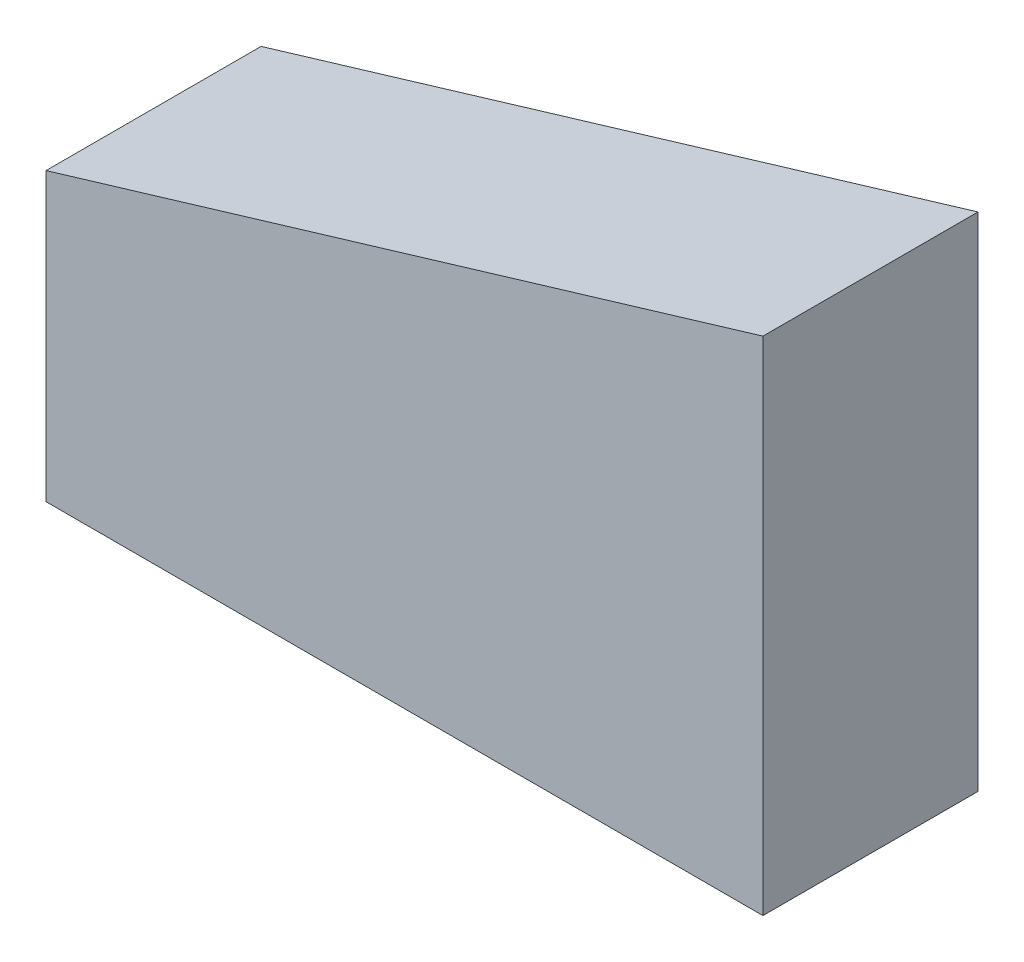
SolidWorks part; units mm, degrees
ref_plane "Front Plane" through (0, 0, 0) normal (0, 0, 1) x (1, 0, 0)
ref_plane "Top Plane" through (0, 0, 0) normal (0, 1, 0) x (1, 0, 0)
ref_plane "Right Plane" through (0, 0, 0) normal (1, 0, 0) x (0, 0, -1)
sketch "Sketch1" plane through (0, 0, 0) normal (0, 0, 1) x (1, 0, 0)
  line L0 (-26.8167, 0.0379) -> (36.6833, 19.0879)
  line L1 (-26.8167, -25.3621) -> (36.6833, -25.3621)
  line L2 (-26.8167, -25.3621) -> (-26.8167, 0.0379)
  line L4 (36.6833, -25.3621) -> (36.6833, 19.0879)
  dimension "D1" = 63.5
  dimension "D2" = 25.4
  dimension "D3" = 44.45
extrude "Boss-Extrude1" add sketch "Sketch1" along normal blind 19.05
